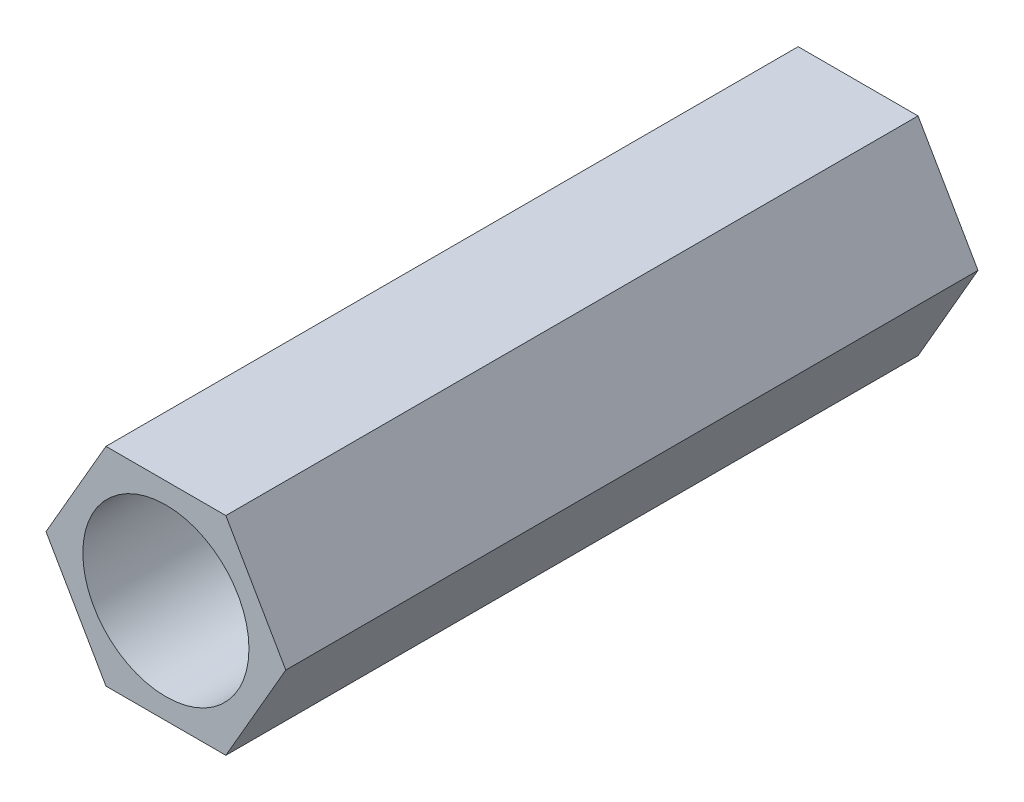
SolidWorks part; units mm, degrees
ref_plane "정면" through (0, 0, 0) normal (0, 0, 1) x (1, 0, 0)
ref_plane "윗면" through (0, 0, 0) normal (0, 1, 0) x (1, 0, 0)
ref_plane "우측면" through (0, 0, 0) normal (1, 0, 0) x (0, 0, -1)
sketch "스케치1" plane through (0, 0, 0) normal (0, 0, 1) x (1, 0, 0)
  line L1 (0.866, -1.5) -> (1.7321, 0)
  line L2 (1.7321, 0) -> (0.866, 1.5)
  line L3 (0.866, 1.5) -> (-0.866, 1.5)
  line L4 (-0.866, 1.5) -> (-1.7321, 0)
  line L5 (-1.7321, 0) -> (-0.866, -1.5)
  line L6 (-0.866, -1.5) -> (0.866, -1.5)
  circle A0 centre (0, 0) radius 1.5 construction
  dimension "D1" = 3
extrude "보스-돌출1" add sketch "스케치1" along normal blind 10
sketch "스케치3" plane through (0, 0, 0) normal (0, 0, -1) x (-1, 0, 0)
  point P0 (0, 0)
hole_wizard "M2 여유 구멍1" positions "스케치6" profile "스케치7" hole size "M2" standard "Ansi Metric" end condition through all
sketch "스케치6" plane through (0, 0, 0) normal (0, 0, -1) x (-1, 0, 0)
  point P0 (0, 0)
sketch "스케치7" plane through (0, 0, 0) normal (1, 0, 0) x (0, 1, 0)
  line L0 (0, 0) -> (0, 10)
  line L1 (0, 10) -> (1.2, 10)
  line L2 (1.2, 10) -> (1.2, 0)
  line L5 (1.2, 0) -> (0, 0)
  line L11 (0, -6.35) -> (0, 107.95) construction
  dimension "관통 구멍 지름" = 2.4
  dimension "관통 구멍 깊이" = 10
